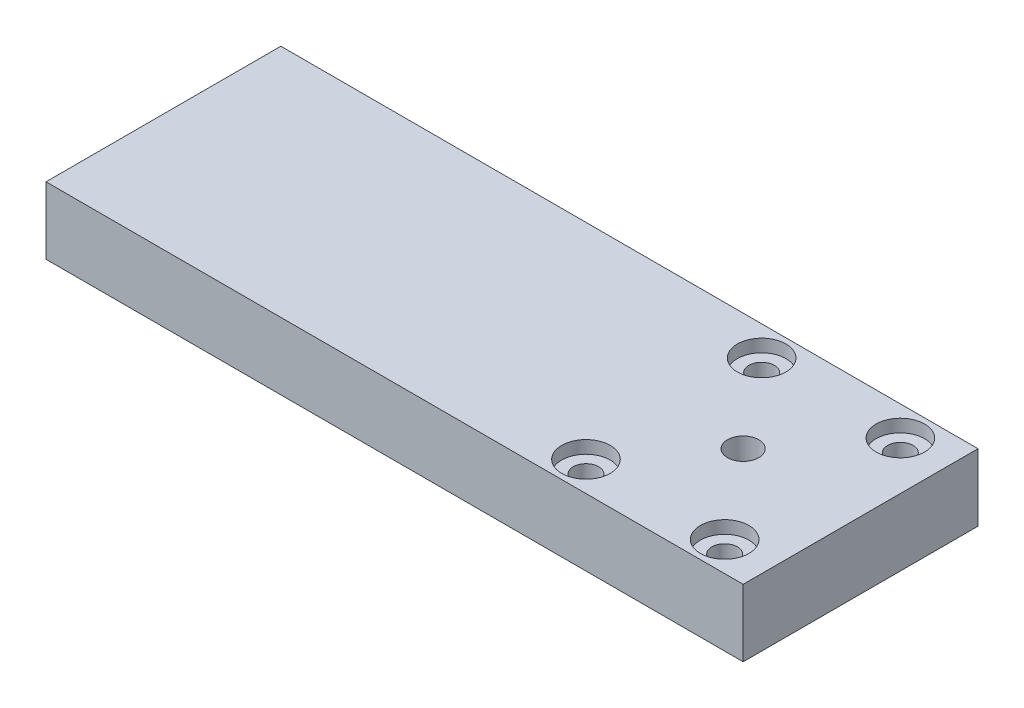
SolidWorks part; units mm, degrees
material "6061 Alloy"
ref_plane "Front" through (0, 0, 0) normal (0, 0, 1) x (1, 0, 0)
ref_plane "Top" through (0, 0, 0) normal (0, 1, 0) x (1, 0, 0)
ref_plane "Right" through (0, 0, 0) normal (1, 0, 0) x (0, 0, -1)
sketch "Sketch1" plane through (0, 0, 0) normal (0, 1, 0) x (1, 0, 0)
  line L1 (-25.4, -25.4) -> (25.4, -25.4)
  line L2 (-25.4, -25.4) -> (-25.4, 25.4)
  line L3 (-25.4, 25.4) -> (25.4, 25.4)
  line L4 (25.4, -25.4) -> (25.4, 25.4)
  line L5 (-25.4, -25.4) -> (25.4, 25.4) construction
  line L6 (-25.4, 25.4) -> (25.4, -25.4) construction
  point P0 (0, 0)
  dimension "D1" = 50.8
  dimension "D2" = 50.8
extrude "Boss-Extrude1" add sketch "Sketch1" along normal mid plane 14.52
hole_wizard "CBORE for M5 SBHCS1" positions "Sketch2" profile "Sketch3" counterbore size "M5" standard "ANSI Metric" end condition up to next
sketch "Sketch2" plane through (0, 7.26, 0) normal (0, 1, 0) x (1, 0, 0)
  line L0 (15, -19) -> (-15, 19) construction
  point P0 (-15, 19)
  point P2 (-15, -19)
  point P4 (15, -19)
  point P6 (15, 19)
  dimension "D1" = 30
  dimension "D2" = 38
sketch "Sketch3" plane through (-15, 7.26, -19) normal (1, 0, 0) x (0, 0, 1)
  line L0 (0, 0) -> (0, 14.52)
  line L1 (0, 14.52) -> (2.75, 14.52)
  line L3 (2.75, 14.52) -> (2.75, 2.75)
  line L4 (2.75, 2.75) -> (5.25, 2.75)
  line L5 (5.25, 2.75) -> (5.25, 0)
  line L7 (5.25, 0) -> (0, 0)
  line L11 (0, -6.35) -> (0, 107.95) construction
  dimension "Thru Hole Dia." = 5.5
  dimension "Thru Hole Depth" = 14.52
  dimension "C'Bore Dia." = 10.5
  dimension "C'Bore Depth" = 2.75
hole_wizard "CBORE for 1/4 Socket Head Cap Screw1" positions "Sketch4" profile "Sketch5" counterbore size "1/4" standard "ANSI Inch" end condition up to next
sketch "Sketch4" plane through (0, -7.26, 0) normal (0, 1, 0) x (1, 0, 0)
  point P0 (0, 0)
sketch "Sketch5" plane through (0, -7.26, 0) normal (1, 0, 0) x (0, 0, -1)
  line L0 (0, 0) -> (0, 14.52)
  line L1 (0, 14.52) -> (3.3782, 14.52)
  line L3 (3.3782, 14.52) -> (3.3782, 6.35)
  line L4 (3.3782, 6.35) -> (5.5562, 6.35)
  line L5 (5.5562, 6.35) -> (5.5562, 0)
  line L7 (5.5562, 0) -> (0, 0)
  line L11 (0, -6.35) -> (0, 107.95) construction
  dimension "Thru Hole Dia." = 6.7564
  dimension "Thru Hole Depth" = 14.52
  dimension "C'Bore Dia." = 11.1125
  dimension "C'Bore Depth" = 6.35
sketch "Sketch6" plane through (-25.4, 0, 0) normal (-1, 0, 0) x (0, 0, 1)
  line L1 (-25.4, 7.26) -> (25.4, 7.26)
  line L2 (-25.4, 7.26) -> (-25.4, -7.26)
  line L3 (-25.4, -7.26) -> (25.4, -7.26)
  line L4 (25.4, 7.26) -> (25.4, -7.26)
extrude "Boss-Extrude2" add sketch "Sketch6" along normal blind 100
